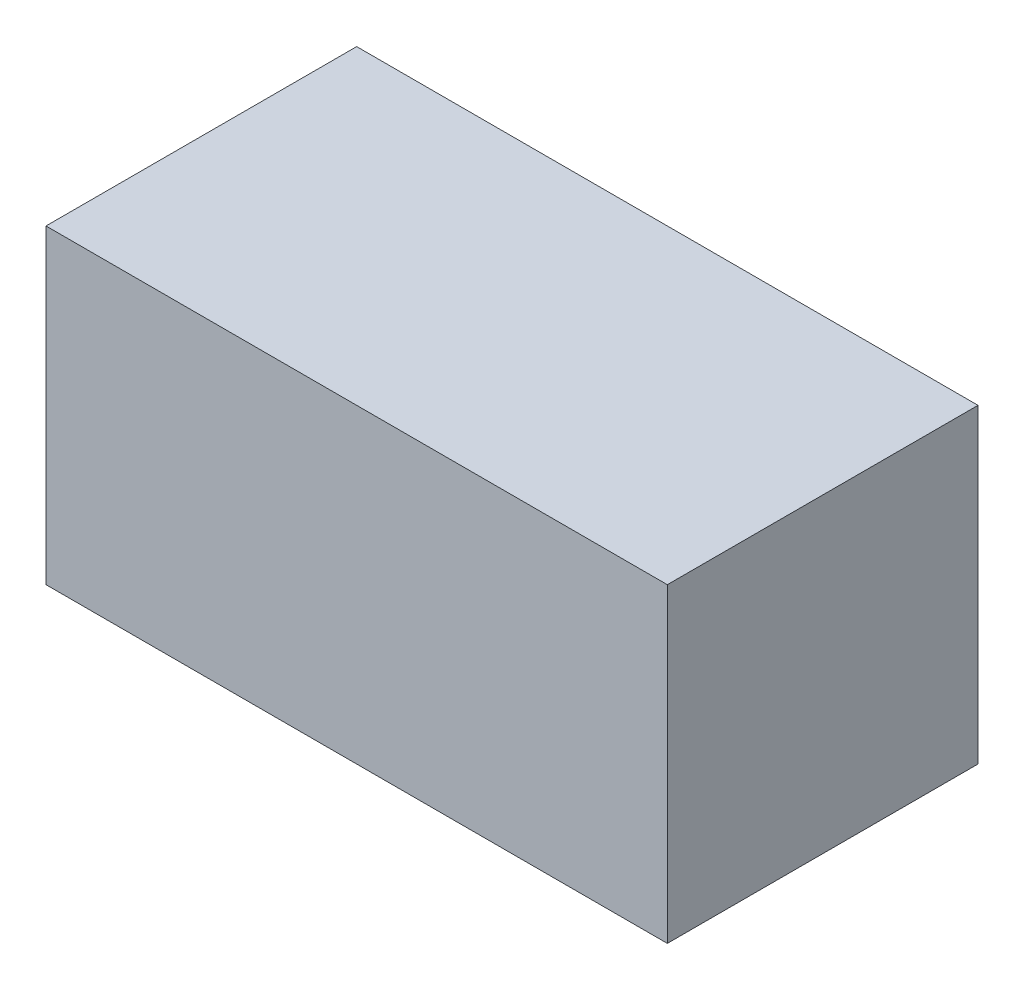
SolidWorks part; units mm, degrees
ref_plane "Front Plane" through (0, 0, 0) normal (0, 0, 1) x (1, 0, 0)
ref_plane "Top Plane" through (0, 0, 0) normal (0, 1, 0) x (1, 0, 0)
ref_plane "Right Plane" through (0, 0, 0) normal (1, 0, 0) x (0, 0, -1)
sketch "Sketch1" plane through (0, 0, 0) normal (0, 1, 0) x (1, 0, 0)
  line L1 (0, 0) -> (1.016, 0)
  line L2 (0, 0) -> (0, 0.508)
  line L3 (0, 0.508) -> (1.016, 0.508)
  line L4 (1.016, 0) -> (1.016, 0.508)
  dimension "D1" = 1.016
  dimension "D2" = 0.508
extrude "Boss-Extrude1" add sketch "Sketch1" along normal blind 0.508
